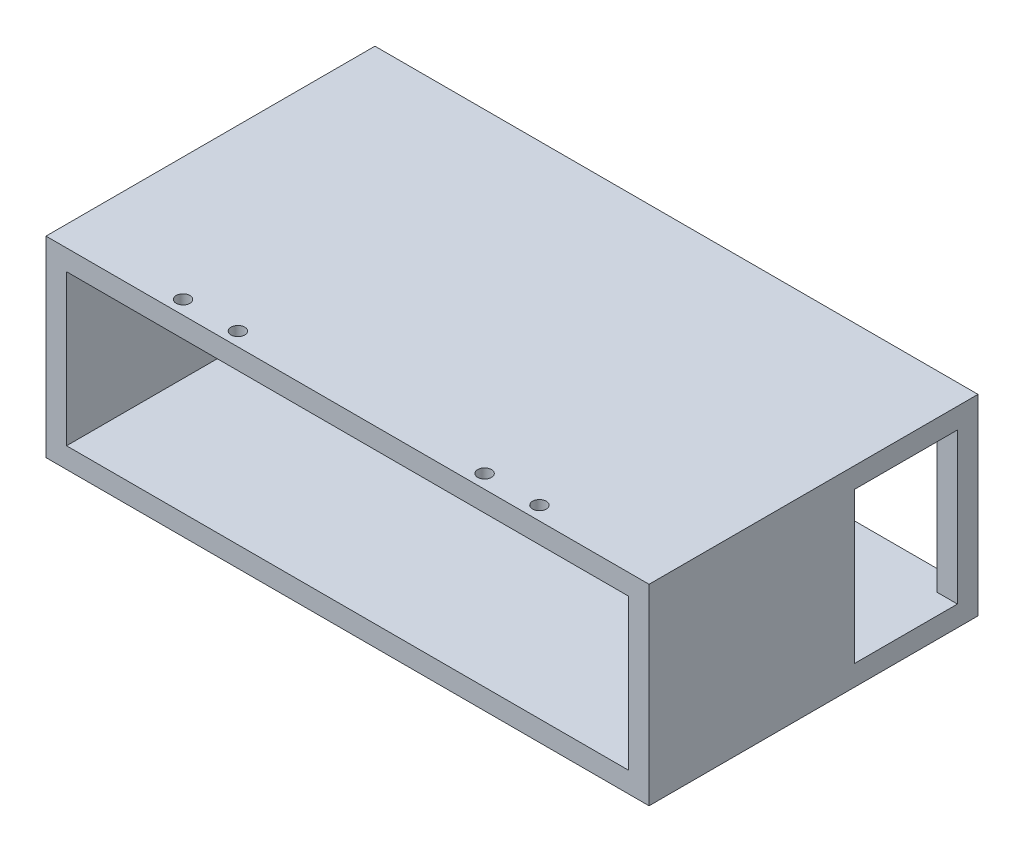
SolidWorks part; units mm, degrees
material "自訂玻璃纖維"
ref_plane "前基準面" through (0, 0, 0) normal (0, 0, 1) x (1, 0, 0)
ref_plane "上基準面" through (0, 0, 0) normal (0, 1, 0) x (1, 0, 0)
ref_plane "右基準面" through (0, 0, 0) normal (1, 0, 0) x (0, 0, -1)
sketch "草圖1" plane through (0, 0, 0) normal (0, 0, 1) x (1, 0, 0)
  line L1 (-57.6748, 35.7154) -> (30.3252, 35.7154)
  line L2 (-57.6748, 35.7154) -> (-57.6748, 7.7154)
  line L3 (-57.6748, 7.7154) -> (30.3252, 7.7154)
  line L4 (30.3252, 35.7154) -> (30.3252, 7.7154)
  dimension "D1" = 88
  dimension "D2" = 28
extrude "填料-伸長1" add sketch "草圖1" along normal blind 48
shell "薄殼1" thickness 3
sketch "草圖2" plane through (0, 35.7154, 0) normal (0, 1, 0) x (1, 0, 0)
  line L0 (30.3252, -48) -> (-57.6748, -48) construction
  circle A0 centre (-31.6748, -46) radius 1
  circle A1 centre (-39.6748, -46) radius 1
  circle A2 centre (12.3252, -46) radius 1
  circle A3 centre (4.3252, -46) radius 1
  point P6 (-13.6748, -48)
  dimension "D1" = 2
  dimension "D2" = 2
  dimension "D3" = 8
  dimension "D4" = 18
  dimension "D5" = 2
  dimension "D6" = 2
  dimension "D7" = 18
  dimension "D8" = 8
  dimension "D9" = 2
extrude "除料-伸長1" cut sketch "草圖2" against normal blind 3
sketch "草圖5" plane through (-57.6748, 0, 0) normal (-1, 0, 0) x (0, 0, 1)
  line L0 (48, 35.7154) -> (0, 35.7154) construction
  line L1 (3, 32.7154) -> (18, 32.7154)
  line L2 (3, 32.7154) -> (3, 10.7154)
  line L3 (3, 10.7154) -> (18, 10.7154)
  line L4 (18, 32.7154) -> (18, 10.7154)
  line L5 (0, 35.7154) -> (0, 7.7154) construction
  line L6 (48, 7.7154) -> (0, 7.7154) construction
  dimension "D1" = 3
  dimension "D2" = 3
  dimension "D3" = 3
  dimension "D4" = 15
extrude "除料-伸長4" cut sketch "草圖5" against normal through all
sketch "草圖6" plane through (0, 0, 0) normal (0, 0, -1) x (-1, 0, 0)
  line L0 (-30.3252, 35.7154) -> (57.6748, 35.7154) construction
  line L1 (-27.3252, 32.7154) -> (-12.3252, 32.7154)
  line L2 (-27.3252, 32.7154) -> (-27.3252, 10.7154)
  line L3 (-27.3252, 10.7154) -> (-12.3252, 10.7154)
  line L4 (-12.3252, 32.7154) -> (-12.3252, 10.7154)
  line L5 (39.6748, 32.7154) -> (54.6748, 32.7154)
  line L6 (39.6748, 32.7154) -> (39.6748, 10.7154)
  line L7 (39.6748, 10.7154) -> (54.6748, 10.7154)
  line L8 (54.6748, 32.7154) -> (54.6748, 10.7154)
  line L9 (-30.3252, 7.7154) -> (-30.3252, 35.7154) construction
  line L10 (57.6748, 7.7154) -> (-30.3252, 7.7154) construction
  line L11 (57.6748, 35.7154) -> (57.6748, 7.7154) construction
  dimension "D1" = 15
  dimension "D2" = 3
  dimension "D3" = 3
  dimension "D4" = 3
  dimension "D5" = 15
  dimension "D6" = 3
  dimension "D7" = 3
  dimension "D8" = 3
extrude "除料-伸長5" cut sketch "草圖6" against normal blind 15
